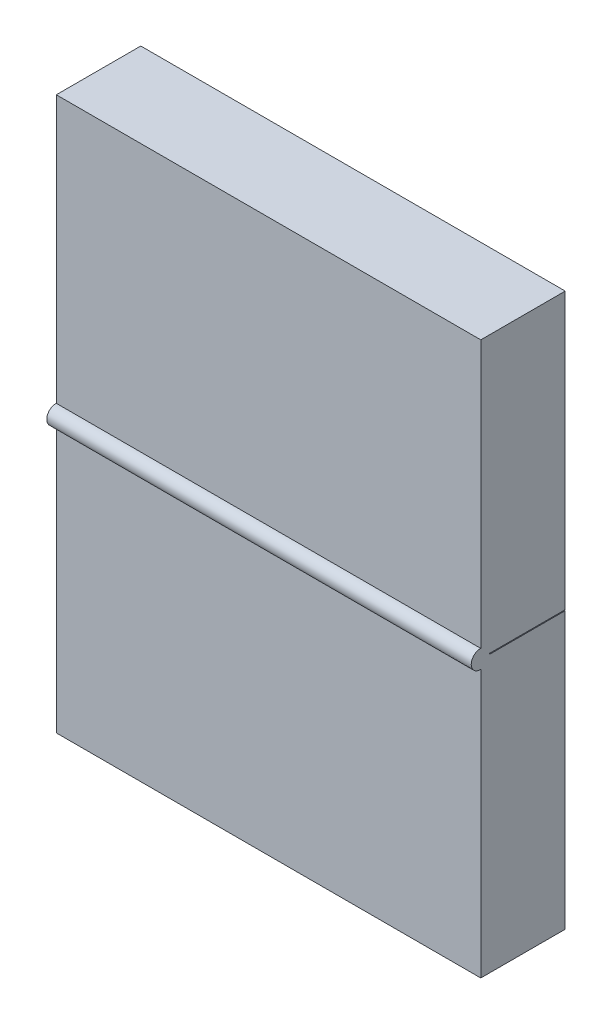
SolidWorks part; units mm, degrees
ref_plane "Front" through (0, 0, 0) normal (0, 0, 1) x (1, 0, 0)
ref_plane "Top" through (0, 0, 0) normal (0, 1, 0) x (1, 0, 0)
ref_plane "Right" through (0, 0, 0) normal (1, 0, 0) x (0, 0, -1)
sketch "Joint Guide" plane through (0, 0, 0) normal (1, 0, 0) x (0, 0, -1)
  line L0 (0, 0) -> (1, 0) construction
  line L1 (1, 0) -> (1.15, 0) construction
  line L2 (1.15, 0) -> (2.15, 0) construction
  circle A0 centre (0, 0) radius 1
  circle A1 centre (0, 0) radius 1.15
  circle A2 centre (0, 0) radius 2.15
  dimension "D1" = 2
  dimension "D2" = 0.15
  dimension "D3" = 1
sketch "Sketch2" plane through (0, 0, 0) normal (1, 0, 0) x (0, 0, -1)
  line L0 (2.1477, 0.1) -> (20, 0.1)
  line L1 (20, 0.1) -> (20, 65.1)
  line L2 (20, 65.1) -> (0.1, 65.1)
  line L3 (0.1, 65.1) -> (0.1, 2.1477)
  line L4 (0, 0) -> (0, 23.21) construction
  line L5 (0, 0) -> (17.7231, 0) construction
  line L6 (20, -65.1) -> (0.1, -65.1)
  line L7 (20, -0.1) -> (20, -65.1)
  line L8 (2.1477, -0.1) -> (20, -0.1)
  line L9 (0.1, -65.1) -> (0.1, -2.1477)
  circle A0 centre (0, 0) radius 2.15 construction
  arc A1 (0.1, 2.1477) -> (2.1477, 0.1) centre (0, 0) ccw
  arc A2 (0.1, -2.1477) -> (2.1477, -0.1) centre (0, 0) cw
  dimension "D1" = 0.2
  dimension "D2" = 0.2
  dimension "D3" = 40
  dimension "D4" = 65
extrude "Boss-Extrude1" add sketch "Sketch2" along normal mid plane 100 contours L3 A2 L0 L1 L2 | A1 L9 L6 L7 L8
